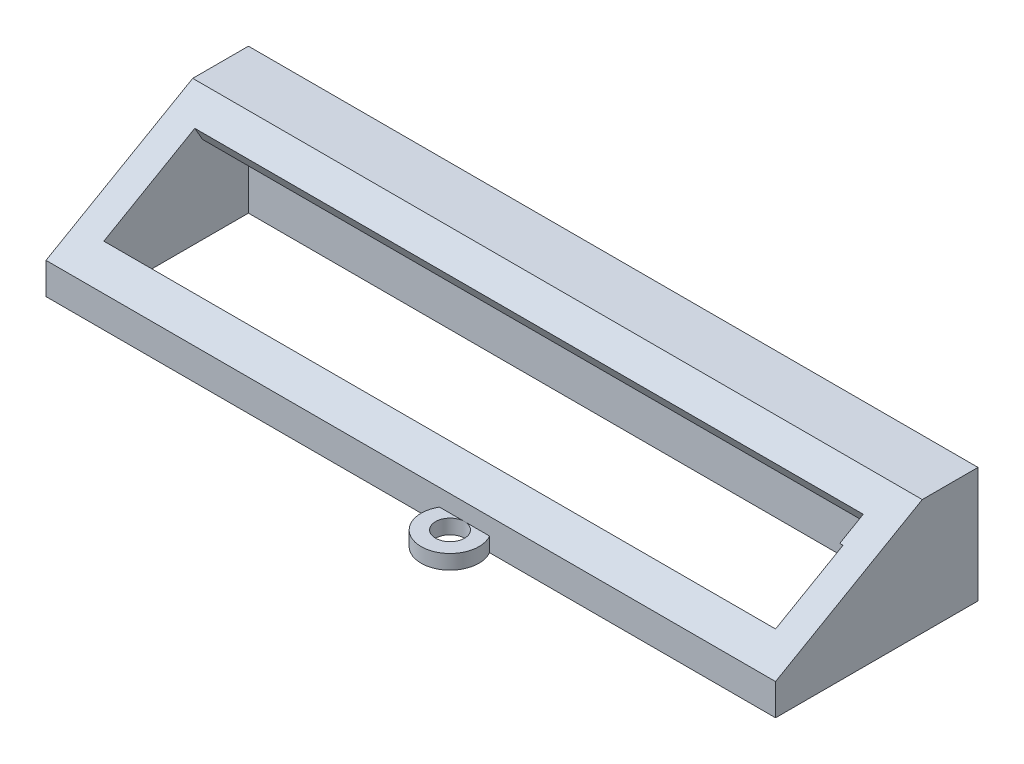
SolidWorks part; units mm, degrees
ref_plane "前基準面" through (0, 0, 0) normal (0, 0, 1) x (1, 0, 0)
ref_plane "上基準面" through (0, 0, 0) normal (0, 1, 0) x (1, 0, 0)
ref_plane "右基準面" through (0, 0, 0) normal (1, 0, 0) x (0, 0, -1)
sketch "草圖1" plane through (0, 0, 0) normal (0, 1, 0) x (1, 0, 0)
  line L1 (-252.27, 70) -> (252.27, 70)
  line L2 (-252.27, 70) -> (-252.27, -70)
  line L3 (-252.27, -70) -> (252.27, -70)
  line L4 (252.27, 70) -> (252.27, -70)
  line L5 (-252.27, 70) -> (252.27, -70) construction
  line L6 (-252.27, -70) -> (252.27, 70) construction
  point P0 (0, 0)
  dimension "D1" = 504.54
  dimension "D2" = 140
extrude "填料-伸長1" add sketch "草圖1" along normal blind 80
sketch "草圖2" plane through (0, 0, 0) normal (0, -1, 0) x (1, 0, 0)
  line L0 (-252.27, 70) -> (252.27, 70) construction
  line L1 (232.27, 50) -> (-232.27, 50)
  line L2 (232.27, 50) -> (232.27, -50)
  line L3 (232.27, -50) -> (-232.27, -50)
  line L4 (-232.27, 50) -> (-232.27, -50)
  line L5 (232.27, 50) -> (-232.27, -50) construction
  line L6 (232.27, -50) -> (-232.27, 50) construction
  line L7 (252.27, 70) -> (252.27, -70) construction
  point P0 (0, 0)
  dimension "D1" = 20
  dimension "D2" = 20
extrude "除料-伸長1" cut sketch "草圖2" against normal blind 60
sketch "草圖7" plane through (252.27, 0, 0) normal (1, 0, 0) x (0, 0, -1)
  line L0 (-70, 21.7294) -> (31.4571, 80)
  line L1 (-70, 80) -> (-70, 0) construction
  line L2 (-70, 80) -> (70, 80) construction
  line L3 (31.4571, 80) -> (-70, 80)
  line L4 (-70, 80) -> (-70, 21.7294)
extrude "除料-伸長2" cut sketch "草圖7" against normal through all
sketch "草圖8" plane through (0, 46.571, 26.7474) normal (0, 0.8672, 0.498) x (1, 0, 0)
  line L1 (-232.27, 26.9638) -> (230, 26.9638)
  line L2 (-232.27, 26.9638) -> (-232.27, 45.7291)
  line L3 (-232.27, 45.7291) -> (230, 45.7291)
  line L4 (230, 26.9638) -> (230, 45.7291)
extrude "除料-伸長3" cut sketch "草圖8" against normal blind 15
sketch "草圖12" plane through (0, 0, 0) normal (0, -1, 0) x (1, 0, 0)
  line L0 (-969.6372, 80) -> (49030.3628, 80) construction
  circle A0 centre (37.1617, 80) radius 10
extrude "伸長-薄件2" add sketch "草圖12" against normal blind 10 thin
